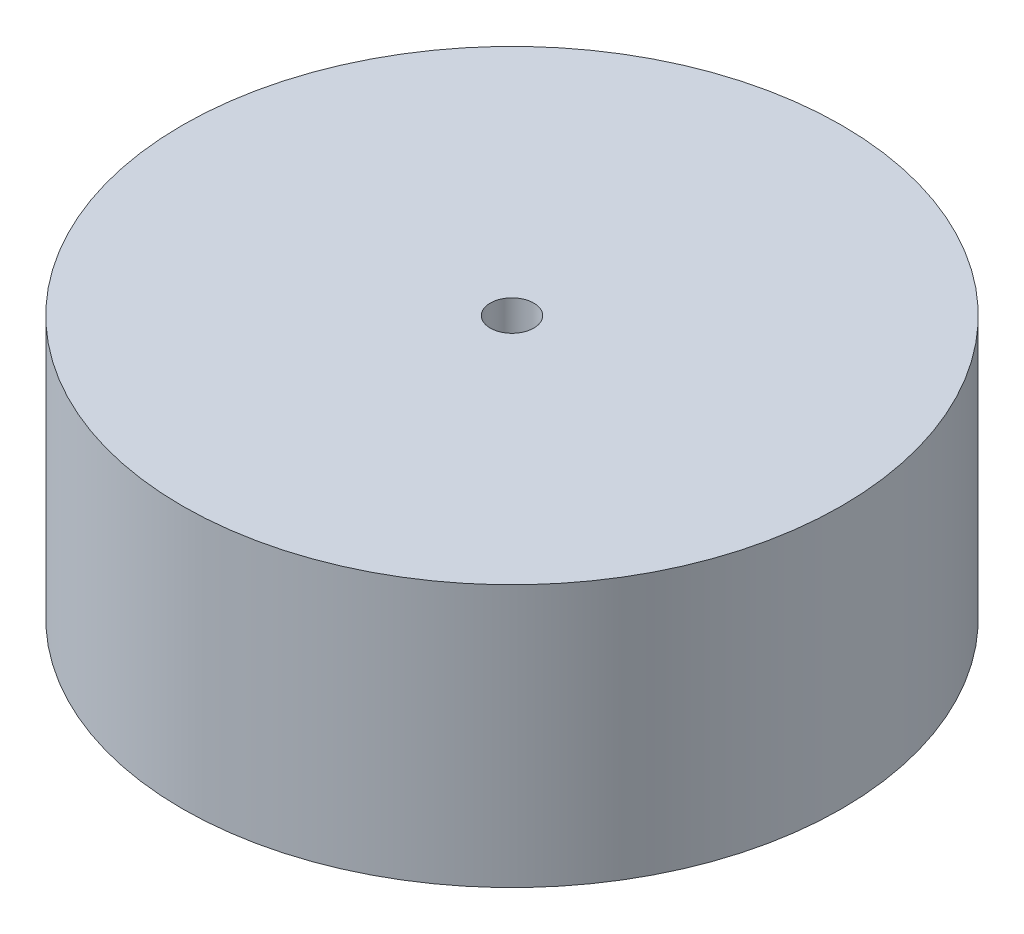
SolidWorks part; units mm, degrees
ref_plane "Front Plane" through (0, 0, 0) normal (0, 0, 1) x (1, 0, 0)
ref_plane "Top Plane" through (0, 0, 0) normal (0, 1, 0) x (1, 0, 0)
ref_plane "Right Plane" through (0, 0, 0) normal (1, 0, 0) x (0, 0, -1)
sketch "Sketch1" plane through (0, 0, 0) normal (0, 1, 0) x (1, 0, 0)
  circle A0 centre (0, 0) radius 22
  dimension "D1" = 44
extrude "Boss-Extrude1" add sketch "Sketch1" along normal blind 17.5
sketch "Sketch2" plane through (0, 17.5, 0) normal (0, 1, 0) x (1, 0, 0)
  circle A0 centre (0, 0) radius 1.45
  dimension "D1" = 2.9
extrude "Cut-Extrude1" cut sketch "Sketch2" against normal up to next
